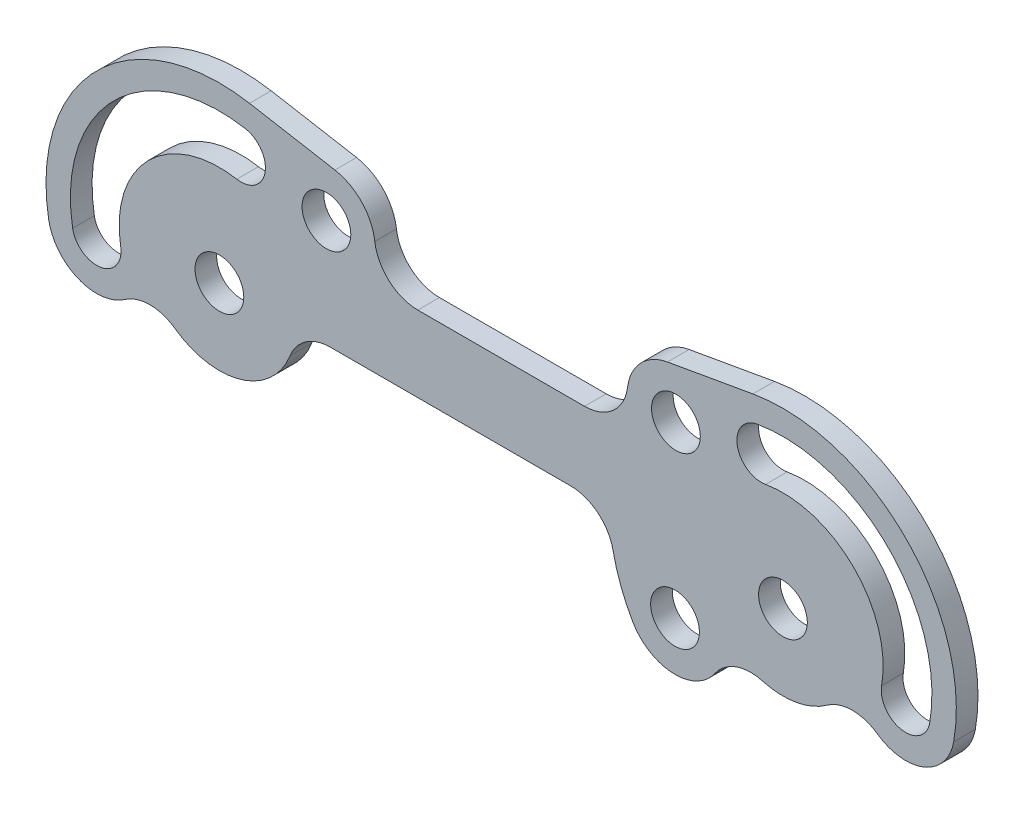
SolidWorks part; units mm, degrees
ref_plane "Front Plane" through (0, 0, 0) normal (0, 0, 1) x (1, 0, 0)
ref_plane "Top Plane" through (0, 0, 0) normal (0, 1, 0) x (1, 0, 0)
ref_plane "Right Plane" through (0, 0, 0) normal (1, 0, 0) x (0, 0, -1)
sketch "Sketch1" plane through (0, 0, 0) normal (0, 0, 1) x (1, 0, 0)
  line L0 (20.6375, 0) -> (-20.6375, 0)
  line L1 (-20.6375, 0) -> (-20.6375, 5.5562) construction
  line L2 (-20.6375, 0) -> (-18.4322, 12.5071) construction
  line L3 (-20.6375, 0) -> (-26.1937, 0) construction
  line L4 (-20.6375, 0) -> (-33.1446, -2.2053) construction
  line L5 (-19.0524, 8.9894) -> (-12.7989, 7.8868) construction
  line L6 (-10.0921, 5.5562) -> (10.0921, 5.5562)
  line L7 (0, 5.5562) -> (0, 0)
  line L8 (-12.1786, 11.4044) -> (-13.4191, 4.3692) construction
  line L9 (-18.4322, 12.5071) -> (-12.1786, 11.4044)
  line L10 (0, 5.5562) -> (0, -5.5619) construction
  line L11 (12.1786, 11.4044) -> (13.4191, 4.3692) construction
  line L12 (19.0524, 8.9894) -> (12.7989, 7.8868) construction
  line L13 (20.6375, 0) -> (33.1446, -2.2053) construction
  line L14 (20.6375, 0) -> (26.1937, 0) construction
  line L15 (20.6375, 0) -> (18.4322, 12.5071) construction
  line L16 (20.6375, 0) -> (20.6375, 5.5562) construction
  line L17 (18.4322, 12.5071) -> (12.1786, 11.4044)
  line L18 (12.7323, -4.5641) -> (20.6375, 0) construction
  circle A0 centre (-20.6375, 0) radius 1.7859
  circle A2 centre (-20.6375, 0) radius 9.1281 construction
  circle A3 centre (-20.6375, 0) radius 5.5562
  circle A4 centre (-19.0524, 8.9894) radius 1.7859
  circle A5 centre (-29.6269, -1.5851) radius 1.7859
  circle A7 centre (-12.7989, 7.8868) radius 1.7859
  circle A8 centre (-29.6269, -1.5851) radius 3.5719
  circle A9 centre (-19.0524, 8.9894) radius 3.5719
  circle A10 centre (-12.7989, 7.8868) radius 3.5719
  arc A11 (-19.3625, 7.2306) -> (-27.8681, -1.275) centre (-20.6375, 0) ccw
  arc A12 (-18.7423, 10.7483) -> (-31.3858, -1.8952) centre (-20.6375, 0) ccw
  arc A13 (-18.4322, 12.5071) -> (-33.1446, -2.2053) centre (-20.6375, 0) ccw
  circle A14 centre (20.6375, 0) radius 9.1281 construction
  arc A15 (18.4322, 12.5071) -> (33.1446, -2.2053) centre (20.6375, 0) cw
  arc A16 (18.7423, 10.7483) -> (31.3858, -1.8952) centre (20.6375, 0) cw
  arc A17 (19.3625, 7.2306) -> (27.8681, -1.275) centre (20.6375, 0) cw
  circle A18 centre (12.7989, 7.8868) radius 3.5719
  circle A19 centre (19.0524, 8.9894) radius 3.5719
  circle A20 centre (29.6269, -1.5851) radius 3.5719
  circle A21 centre (12.7989, 7.8868) radius 1.7859
  circle A22 centre (29.6269, -1.5851) radius 1.7859
  circle A23 centre (19.0524, 8.9894) radius 1.7859
  circle A24 centre (20.6375, 0) radius 5.5562
  circle A25 centre (20.6375, 0) radius 1.7859
  circle A26 centre (12.7323, -4.5641) radius 3.5719
  circle A27 centre (12.7323, -4.5641) radius 1.7859
  arc A28 (9.639, -6.35) -> (7.9375, 0) centre (20.6375, 0) cw
  dimension "D1" = 3.5719
  dimension "D5" = 11.1125
  dimension "D6" = 7.1437
  dimension "D2" = 20.6375
  dimension "D3" = 10
  dimension "D4" = 10
  dimension "D7" = 6.35
  dimension "D8" = 30
extrude "Boss-Extrude1" add sketch "Sketch1" along normal blind 1.5875
fillet "Fillet1" radius 3.175 7 edges at (-26.1093, -0.9648, 0.7937) (-15.0813, 0, 0.7937) (-10.0921, 5.5562, 0.7937) (26.1093, -0.9648, 0.7937) (15.8256, -2.7781, 0.7937) (10.0921, 5.5562, 0.7937) (7.9375, 0, 0.7937)
